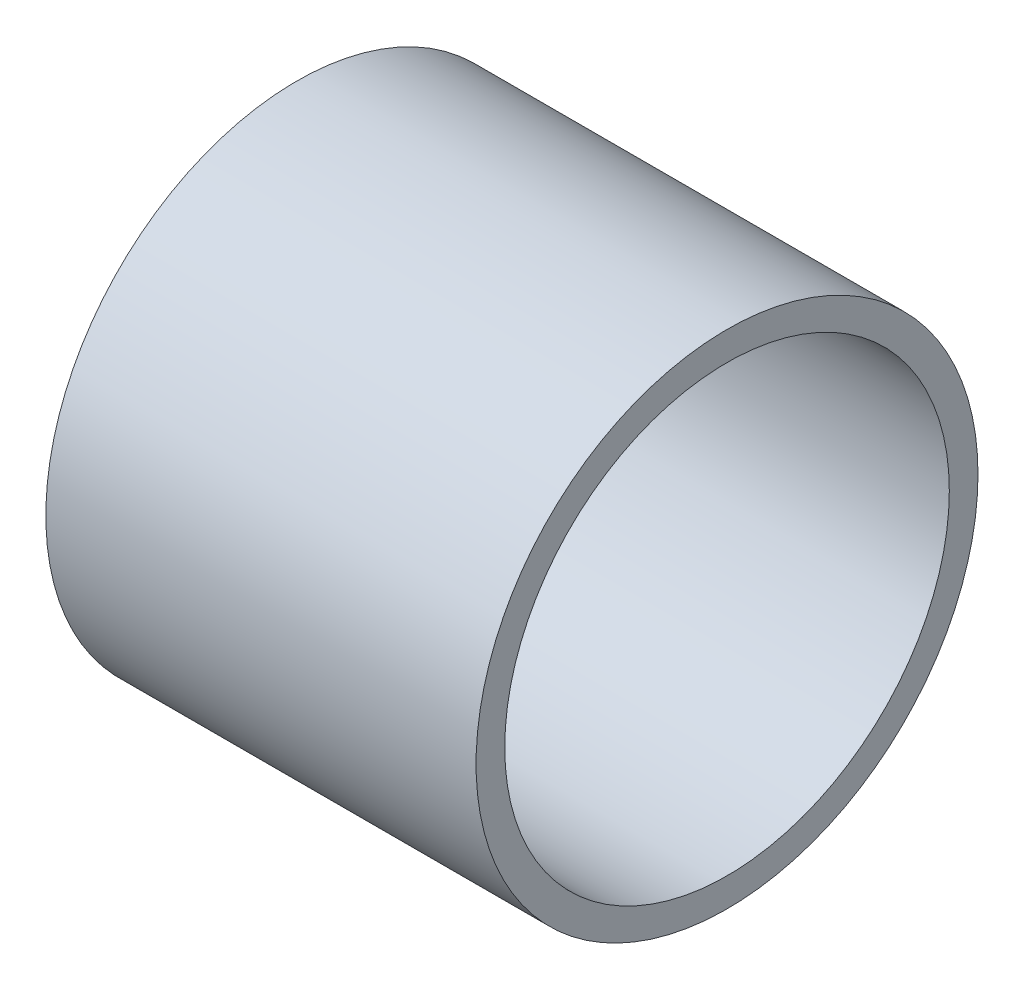
SolidWorks part; units mm, degrees
material "20"
ref_plane "前视基准面" through (0, 0, 0) normal (0, 0, 1) x (1, 0, 0)
ref_plane "上视基准面" through (0, 0, 0) normal (0, 1, 0) x (1, 0, 0)
ref_plane "右视基准面" through (0, 0, 0) normal (1, 0, 0) x (0, 0, -1)
sketch "草图1" plane through (0, 0, 0) normal (1, 0, 0) x (0, 0, -1)
  circle A0 centre (0, 0) radius 35
  circle A1 centre (0, 0) radius 31
  dimension "D1" = 70
  dimension "D2" = 62
extrude "凸台-拉伸1" add sketch "草图1" along normal blind 60
